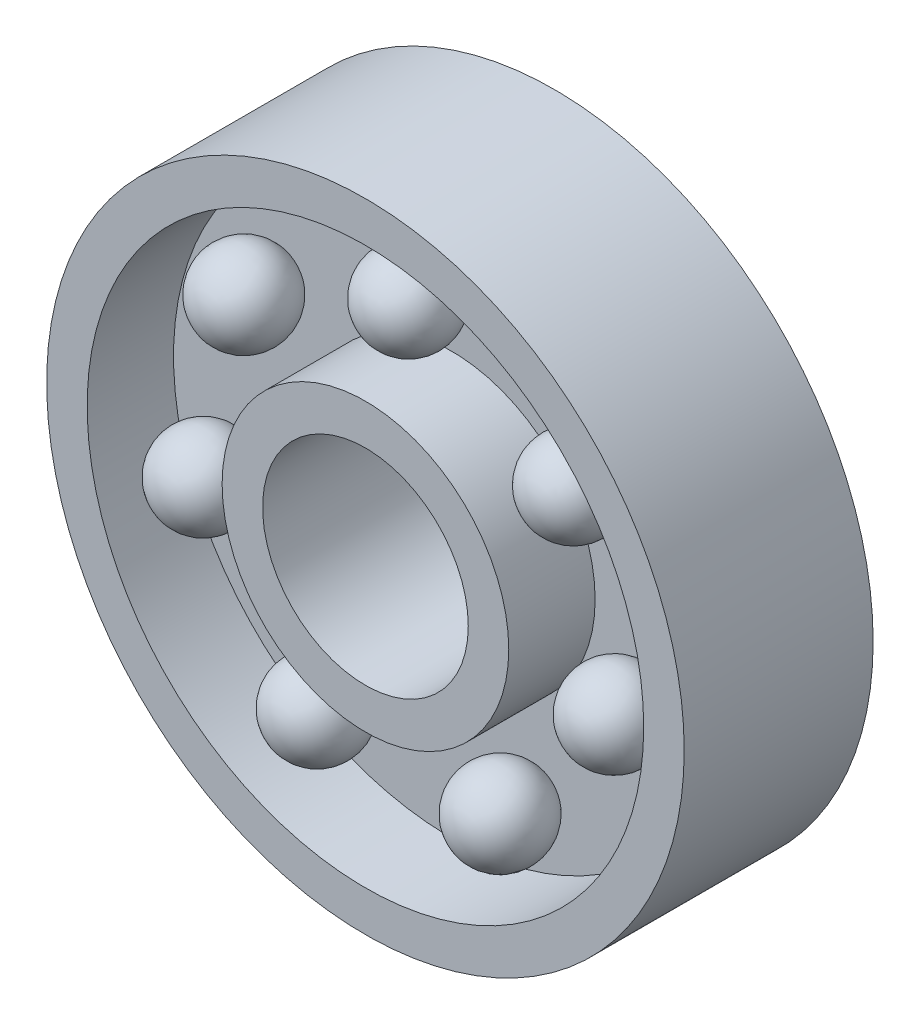
SolidWorks part; units mm, degrees
ref_plane "Front Plane" through (0, 0, 0) normal (0, 0, 1) x (1, 0, 0)
ref_plane "Top Plane" through (0, 0, 0) normal (0, 1, 0) x (1, 0, 0)
ref_plane "Right Plane" through (0, 0, 0) normal (1, 0, 0) x (0, 0, -1)
sketch "Sketch1" plane through (0, 0, 0) normal (1, 0, 0) x (0, 0, -1)
  line L0 (0, 0) -> (-7, 0)
  line L1 (-7, 0) -> (-7, 1.5)
  line L2 (-7, 1.5) -> (-3.8, 1.5)
  line L3 (-3.8, 1.5) -> (-3.8, 6.5)
  line L4 (-3.8, 6.5) -> (-7, 6.5)
  line L5 (-7, 6.5) -> (-7, 8)
  line L6 (-7, 8) -> (0, 8)
  line L7 (0, 8) -> (0, 6.5)
  line L8 (0, 6.5) -> (-3.2, 6.5)
  line L9 (-3.2, 6.5) -> (-3.2, 1.5)
  line L10 (-3.2, 1.5) -> (0, 1.5)
  line L11 (0, 1.5) -> (0, 0)
  line L12 (-3.5, 8) -> (-3.5, 0) construction
  line L13 (-8.7568, -3.81) -> (2.3419, -3.81) construction
  point P17 (0, 4.6142)
  point P18 (-3.25, 6.5)
  dimension "D1" = 7
  dimension "D2" = 5
  dimension "D3" = 3.81
  dimension "D4" = 3.2
  dimension "D5" = 1.5
revolve "Revolve1" add sketch "Sketch1" angle 360 about L13
sketch "Sketch2" plane through (0, 0, 0) normal (1, 0, 0) x (0, 0, -1)
  line L0 (-3.8, 4) -> (-7, 4)
  line L1 (-3.8, 1.5) -> (-3.8, 6.5) construction
  line L2 (-8.1258, 4) -> (-1.1534, 4) construction
  arc A0 (-7, 4) -> (-3.8, 4) centre (-5.4, 4) cw
  dimension "D1" = 1.6
revolve "Revolve3" add sketch "Sketch2" angle 360 about L2
pattern_circular "CirPattern17" count 7 over 360 about axis through (0, -3.81, 0) along (0, 0, 1) of bodies 103
sketch "Sketch3" plane through (0, 0, 0) normal (1, 0, 0) x (0, 0, -1)
  line L0 (-3.2, 6.5) -> (-0.3, 6.5)
  line L2 (-0.3, 6.5) -> (-0.3, 1.5)
  line L3 (-0.3, 1.5) -> (-3.2, 1.5)
  line L4 (-3.2, 1.5) -> (-3.2, 6.5)
  line L5 (-0.3, 4) -> (-3.2, 4) construction
  line L6 (-3.2, 6.5) -> (-3.2, 1.5) construction
  point P2 (-3, 2.75)
  point P9 (-3, 4.2403)
  dimension "D1" = 5
  dimension "D2" = 2.9
revolve "Revolve4" add sketch "Sketch3" angle 360 about L13
